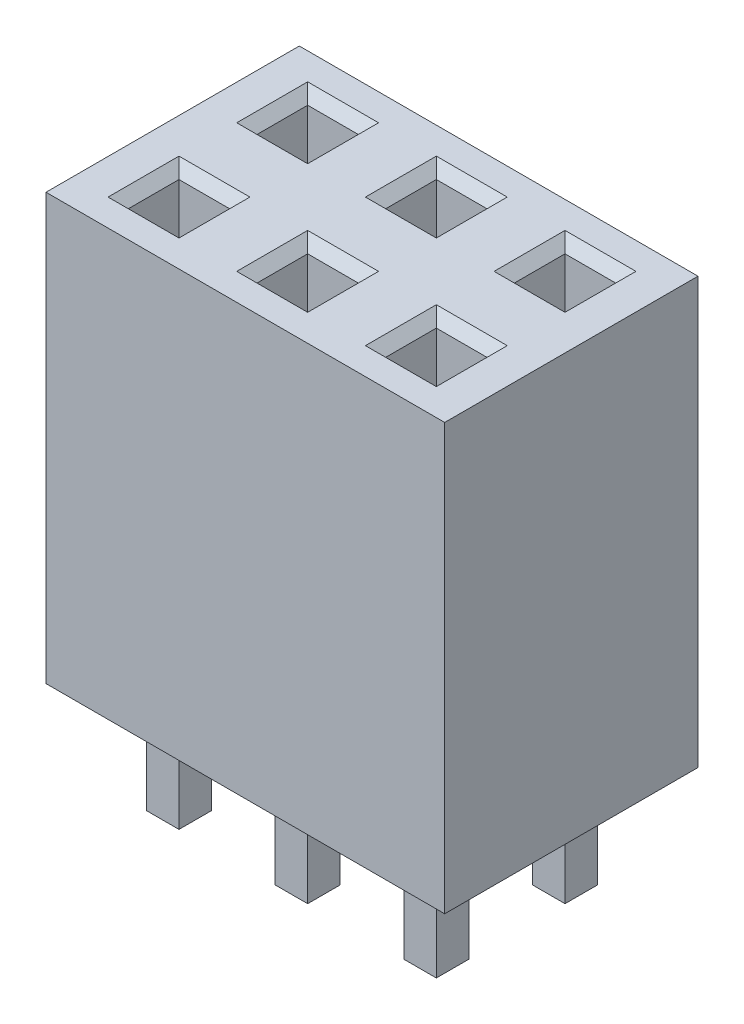
SolidWorks part; units mm, degrees
material "C (Графит)"
ref_plane "Спереди" through (0, 0, 0) normal (0, 0, 1) x (1, 0, 0)
ref_plane "Сверху" through (0, 0, 0) normal (0, 1, 0) x (1, 0, 0)
ref_plane "Справа" through (0, 0, 0) normal (1, 0, 0) x (0, 0, -1)
sketch "Эскиз1" plane through (0, 0, 0) normal (0, 1, 0) x (1, 0, 0)
  line L1 (-1.395, -2.5) -> (1.395, -2.5)
  line L2 (-1.395, -2.5) -> (-1.395, 2.5)
  line L3 (-1.395, 2.5) -> (1.395, 2.5)
  line L4 (1.395, -2.5) -> (1.395, 2.5)
  line L5 (-1.395, -2.5) -> (1.395, 2.5) construction
  line L6 (-1.395, 2.5) -> (1.395, -2.5) construction
  point P0 (0, 0)
  dimension "D1" = 5
  dimension "D2" = 2.79
extrude "Бобышка-Вытянуть1" add sketch "Эскиз1" along normal blind 8.4
sketch "Эскиз2" plane through (0, 8.4, 0) normal (0, 1, 0) x (1, 0, 0)
  line L0 (-1.395, 2.5) -> (-1.395, -2.5) construction
  line L1 (-0.5, 1.77) -> (0.5, 1.77)
  line L2 (-0.5, 1.77) -> (-0.5, 0.77)
  line L3 (-0.5, 0.77) -> (0.5, 0.77)
  line L4 (0.5, 1.77) -> (0.5, 0.77)
  line L5 (-0.5, 1.77) -> (0.5, 0.77) construction
  line L6 (-0.5, 0.77) -> (0.5, 1.77) construction
  line L7 (-1.395, 0) -> (-29.5201, 0) construction
  line L8 (0.5, -1.77) -> (0.5, -0.77)
  line L9 (-0.5, -0.77) -> (0.5, -0.77)
  line L10 (-0.5, -1.77) -> (-0.5, -0.77)
  line L11 (-0.5, -1.77) -> (0.5, -1.77)
  point P0 (0, 1.27)
  dimension "D1" = 1
  dimension "D2" = 1
  dimension "D3" = 1.395
  dimension "D4" = 1.27
extrude "Вырез-Вытянуть1" cut sketch "Эскиз2" against normal blind 8
chamfer "Фаска1" distance 0.2 angle 45 8 edges at (0.5, 8.4, -1.27) (0, 8.4, -0.77) (-0.5, 8.4, -1.27) (0, 8.4, -1.77) (0, 8.4, 1.77) (-0.5, 8.4, 1.27) (0, 8.4, 0.77) (0.5, 8.4, 1.27)
sketch "Эскиз3" plane through (0, 0, 0) normal (0, -1, 0) x (-1, 0, 0)
  line L0 (1.395, 2.5) -> (1.395, -2.5) construction
  line L1 (0.32, 0.95) -> (-0.32, 0.95)
  line L2 (0.32, 0.95) -> (0.32, 1.59)
  line L3 (0.32, 1.59) -> (-0.32, 1.59)
  line L4 (-0.32, 0.95) -> (-0.32, 1.59)
  line L5 (0.32, 0.95) -> (-0.32, 1.59) construction
  line L6 (0.32, 1.59) -> (-0.32, 0.95) construction
  line L7 (1.395, 0) -> (32.9327, 0) construction
  line L8 (0.32, -0.95) -> (-0.32, -0.95)
  line L9 (-0.32, -0.95) -> (-0.32, -1.59)
  line L10 (0.32, -1.59) -> (-0.32, -1.59)
  line L11 (0.32, -0.95) -> (0.32, -1.59)
  point P0 (0, 1.27)
  dimension "D1" = 0.64
  dimension "D2" = 0.64
  dimension "D3" = 1.395
  dimension "D4" = 2.54
extrude "Бобышка-Вытянуть2" add sketch "Эскиз3" along normal blind 2.29
chamfer "Фаска2" distance 0.2 angle 45 8 edges at (0, -2.29, -1.59) (-0.32, -2.29, -1.27) (0, -2.29, -0.95) (0.32, -2.29, -1.27) (0, -2.29, 1.59) (0.32, -2.29, 1.27) (0, -2.29, 0.95) (-0.32, -2.29, 1.27)
pattern_linear "Линейный массив1" count 3 spacing 2.54 along (1, 0, 0) of "Бобышка-Вытянуть1", "Вырез-Вытянуть1", "Фаска1", "Бобышка-Вытянуть2", "Фаска2"
